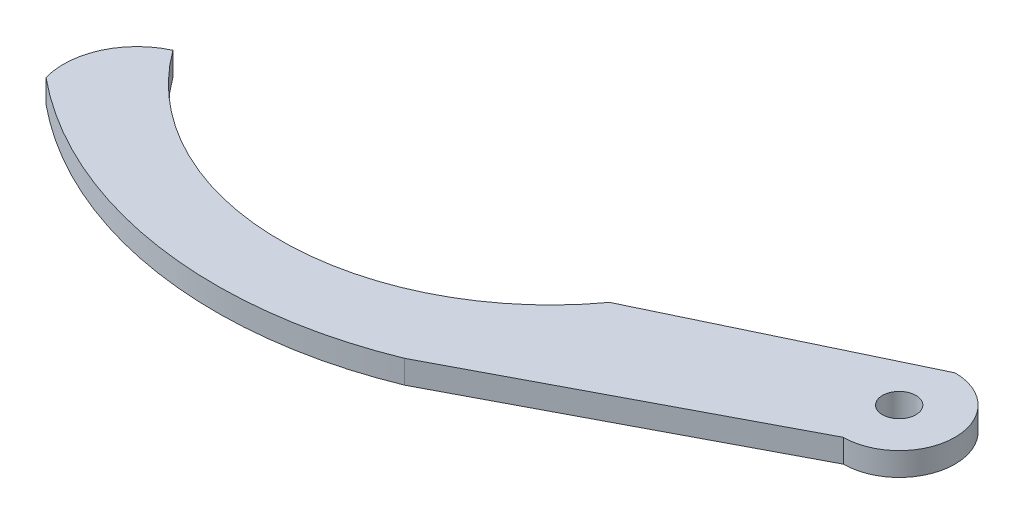
SolidWorks part; units mm, degrees
ref_plane "Front Plane" through (0, 0, 0) normal (0, 0, 1) x (1, 0, 0)
ref_plane "Top Plane" through (0, 0, 0) normal (0, 1, 0) x (1, 0, 0)
ref_plane "Right Plane" through (0, 0, 0) normal (1, 0, 0) x (0, 0, -1)
sketch "Sketch1" plane through (0, 0, 0) normal (0, 1, 0) x (1, 0, 0)
  line L4 (0, -7.62) -> (-101.6, -7.62) construction
  line L5 (-31.8985, -7.62) -> (0, 7.62)
  line L8 (-39.2666, -28.2188) -> (0, -7.62)
  circle A0 centre (0, 0) radius 2.286
  circle A1 centre (0, 0) radius 7.62 construction
  arc A6 (0, 7.62) -> (0, -7.62) centre (0, 0) cw
  arc A7 (-31.8985, -7.62) -> (-91.5017, -7.62) centre (-61.7001, 14.1369) cw
  arc A8 (-91.5017, -7.62) -> (-96.9405, -19.5064) centre (-87.2775, -16.7404) ccw
  arc A9 (-39.2666, -28.2188) -> (-96.9405, -19.5064) centre (-60.8003, 24.4831) cw
  ellipse E0 centre (1010.4022, -622.5816) end of major axis (-129.6908, -67.9188) minor radius 633.9288 (-90.6676, -6.5807) -> (-92.7718, -9.219) ccw construction
  dimension "D1" = 4.572
  dimension "D2" = 15.24
  dimension "D3" = 101.6
extrude "Boss-Extrude1" add sketch "Sketch1" along normal blind 3.175
